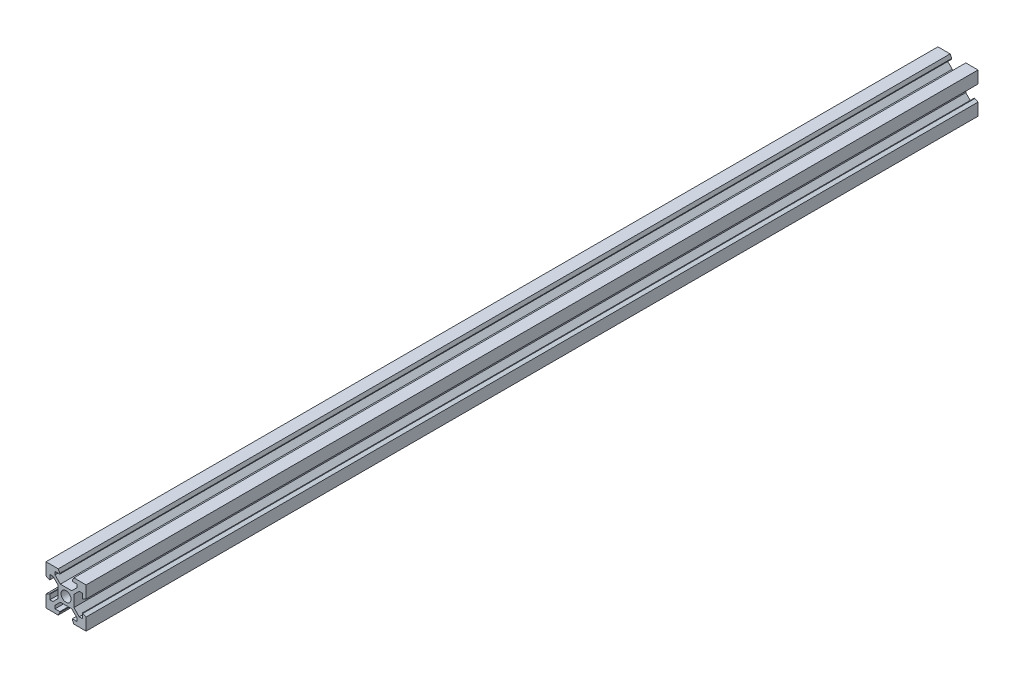
SolidWorks part; units mm, degrees
ref_plane "Front Plane" through (0, 0, 0) normal (0, 0, 1) x (1, 0, 0)
ref_plane "Top Plane" through (0, 0, 0) normal (0, 1, 0) x (1, 0, 0)
ref_plane "Right Plane" through (0, 0, 0) normal (1, 0, 0) x (0, 0, -1)
sketch "Sketch1" plane through (0, 0, 0) normal (0, 0, 1) x (1, 0, 0)
  line L0 (0, 20) -> (0, 13.8958)
  line L1 (0, 0) -> (20, 0)
  line L2 (0, 0) -> (0, 20)
  line L3 (0, 20) -> (20, 20)
  line L4 (20, 0) -> (20, 20)
  line L5 (0, 13.8958) -> (1.56, 13.1)
  line L6 (1.56, 13.1) -> (1.9, 13.1)
  line L7 (1.9, 13.1) -> (1.9, 15.5)
  line L8 (1.9, 15.5) -> (3.4393, 15.5)
  line L9 (3.4393, 15.5) -> (6.2656, 12.6737)
  line L10 (6.2656, 12.6737) -> (7.3263, 13.7344)
  line L11 (7.3263, 13.7344) -> (4.5, 16.5607)
  line L12 (4.5, 16.5607) -> (4.5, 18.1)
  line L13 (4.5, 18.1) -> (6.9, 18.1)
  line L14 (6.9, 18.1) -> (6.9, 18.44)
  line L15 (6.9, 18.44) -> (6.1, 20)
  line L16 (6.1, 20) -> (0, 20)
  line L17 (10, 10) -> (6.1, 13.9)
  line L18 (6.1, 6.1) -> (13.9, 6.1)
  line L19 (6.1, 6.1) -> (6.1, 13.9)
  line L20 (6.1, 13.9) -> (13.9, 13.9)
  line L21 (13.9, 6.1) -> (13.9, 13.9)
  line L22 (6.796, 13.204) -> (4.0494, 15.9506)
  line L23 (10, 10) -> (10, 24.9145) construction
  line L24 (13.1, 18.44) -> (13.9, 20)
  line L25 (13.1, 18.1) -> (13.1, 18.44)
  line L26 (15.5, 18.1) -> (13.1, 18.1)
  line L27 (15.5, 16.5607) -> (15.5, 18.1)
  line L28 (12.6737, 13.7344) -> (15.5, 16.5607)
  line L29 (13.7344, 12.6737) -> (12.6737, 13.7344)
  line L30 (16.5607, 15.5) -> (13.7344, 12.6737)
  line L31 (18.1, 15.5) -> (16.5607, 15.5)
  line L32 (18.1, 13.1) -> (18.1, 15.5)
  line L33 (18.44, 13.1) -> (18.1, 13.1)
  line L34 (20, 13.8958) -> (18.44, 13.1)
  line L35 (10, 10) -> (22.1718, 10)
  line L36 (20, 6.1042) -> (18.44, 6.9)
  line L37 (18.44, 6.9) -> (18.1, 6.9)
  line L38 (18.1, 6.9) -> (18.1, 4.5)
  line L39 (18.1, 4.5) -> (16.5607, 4.5)
  line L40 (16.5607, 4.5) -> (13.7344, 7.3263)
  line L41 (13.7344, 7.3263) -> (12.6737, 6.2656)
  line L42 (12.6737, 6.2656) -> (15.5, 3.4393)
  line L43 (15.5, 3.4393) -> (15.5, 1.9)
  line L44 (15.5, 1.9) -> (13.1, 1.9)
  line L45 (13.1, 1.9) -> (13.1, 1.56)
  line L46 (13.1, 1.56) -> (13.9, 0)
  line L47 (6.9, 1.56) -> (6.1, 0)
  line L48 (6.9, 1.9) -> (6.9, 1.56)
  line L49 (4.5, 1.9) -> (6.9, 1.9)
  line L50 (4.5, 3.4393) -> (4.5, 1.9)
  line L51 (7.3263, 6.2656) -> (4.5, 3.4393)
  line L52 (6.2656, 7.3263) -> (7.3263, 6.2656)
  line L53 (3.4393, 4.5) -> (6.2656, 7.3263)
  line L54 (1.9, 4.5) -> (3.4393, 4.5)
  line L55 (1.9, 6.9) -> (1.9, 4.5)
  line L56 (1.56, 6.9) -> (1.9, 6.9)
  line L57 (0, 6.1042) -> (1.56, 6.9)
  circle A0 centre (10, 10) radius 2.5
  point P21 (2.6697, 15.5)
  dimension "D3" = 5
  dimension "D1" = 20
  dimension "D2" = 20
  dimension "D4" = 10
  dimension "D5" = 10
  dimension "D6" = 7.8
  dimension "D7" = 7.8
  dimension "D8" = 6.1
  dimension "D9" = 6.1
  dimension "D10" = 6.9
  dimension "D11" = 6.9
  dimension "D12" = 6.1042
  dimension "D13" = 6.1
  dimension "D14" = 0.34
  dimension "D15" = 0.34
  dimension "D16" = 1.9
  dimension "D17" = 4.5
  dimension "D18" = 4.5
  dimension "D19" = 1.5
  dimension "D20" = 1.9
extrude "Boss-Extrude1" add sketch "Sketch1" along normal blind 445
